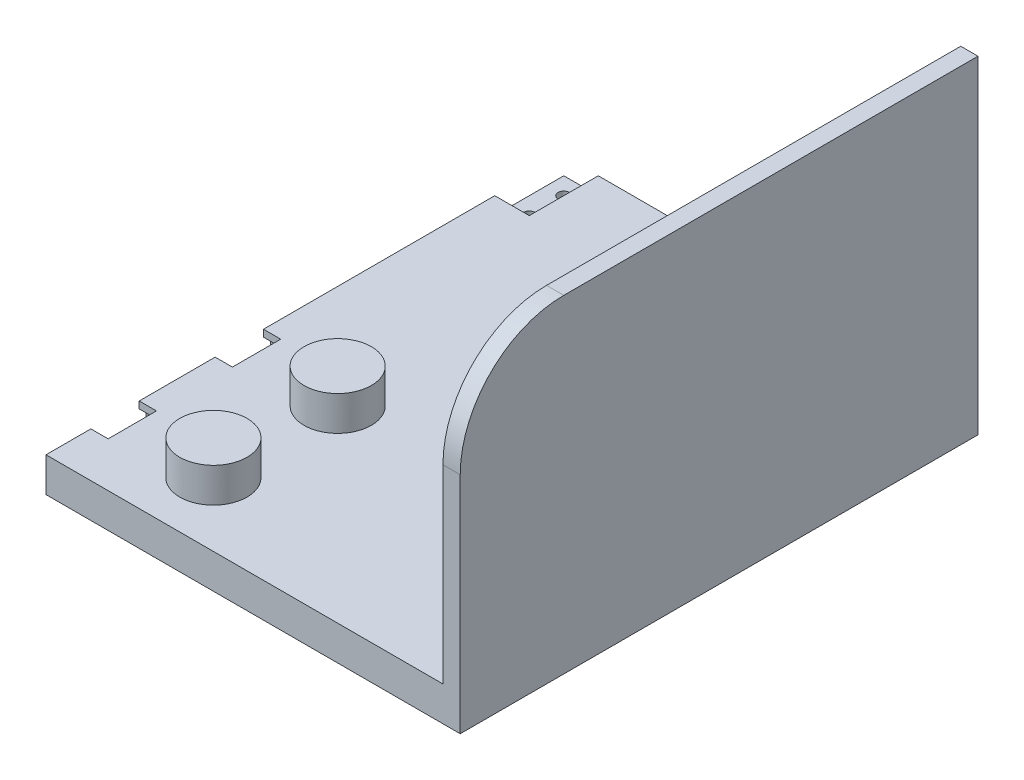
SolidWorks part; units mm, degrees
other "标注1"
sketch "草图4" plane through (-29.3482, 58.8293, 0) normal (-0.5287, 0.6909, -0.493) x (0.7294, 0.6669, 0.1525)
ref_plane "前视基准面" through (0, 0, 0) normal (0, 0, 1) x (1, 0, 0)
ref_plane "上视基准面" through (0, 0, 0) normal (0, 1, 0) x (1, 0, 0)
ref_plane "右视基准面" through (0, 0, 0) normal (1, 0, 0) x (0, 0, -1)
other "Configuration Table"
sketch "草图1" plane through (0, 0, 0) normal (0, 0, 1) x (1, 0, 0)
  line L1 (-29.3482, 58.8293) -> (90.6518, 58.8293)
  line L2 (-29.3482, 58.8293) -> (-29.3482, -36.1707)
  line L3 (-29.3482, -36.1707) -> (90.6518, -36.1707)
  line L4 (90.6518, 58.8293) -> (90.6518, -36.1707)
  dimension "D1" = 120
  dimension "D2" = 95
extrude "凸台-拉伸1" add sketch "草图1" along normal blind 150
sketch "草图2" plane through (0, 0, 150) normal (0, 0, 1) x (1, 0, 0)
  line L0 (-29.3482, -36.1707) -> (90.6518, -36.1707) construction
  line L1 (-29.3482, 58.8293) -> (85.6518, 58.8293)
  line L2 (-29.3482, 58.8293) -> (-29.3482, -26.1707)
  line L3 (-29.3482, -26.1707) -> (85.6518, -26.1707)
  line L4 (85.6518, 58.8293) -> (85.6518, -26.1707)
  line L5 (90.6518, -36.1707) -> (90.6518, 58.8293) construction
  dimension "D1" = 10
  dimension "D2" = 5
extrude "切除-拉伸1" cut sketch "草图2" against normal blind 150
sketch "草图3" plane through (90.6518, 0, 0) normal (1, 0, 0) x (0, 0, -1)
  line L0 (-150, -26.1707) -> (0, 58.8293)
  line L1 (-150, -36.1707) -> (-150, 58.8293) construction
  line L2 (0, 58.8293) -> (0, -36.1707)
  line L3 (0, -36.1707) -> (-150, -36.1707)
  line L4 (-150, -36.1707) -> (-150, -26.1707)
  line L5 (-150, -26.1707) -> (-150, 58.8293)
  line L6 (-150, 58.8293) -> (0, 58.8293)
  line M6 (0, 58.8293) -> (-150, 58.8293)
  line M7 (-150, 58.8293) -> (-150, -36.1707)
  dimension "D1" = 10
extrude "切除-拉伸2" cut sketch "草图3" against normal blind 150 contours L0 M7 M6
sketch "草图5" plane through (0, 0, 0) normal (0, 0, -1) x (-1, 0, 0)
  line L0 (-75.6518, -6.1707) -> (-85.6518, -6.1707)
  line L1 (-75.6518, -6.1707) -> (-75.6518, 28.8293)
  line L2 (-75.6518, 28.8293) -> (-85.6518, 28.8293)
  line L3 (-85.6518, -6.1707) -> (-85.6518, 28.8293)
  line L4 (-85.6518, -26.1707) -> (-85.6518, 58.8293) construction
  line L5 (29.3482, -36.1707) -> (-90.6518, -36.1707) construction
  line L6 (-90.6518, 58.8293) -> (-85.6518, 58.8293) construction
  circle A0 centre (-80.6518, 21.3293) radius 1.65
  circle A1 centre (-80.6518, 11.3293) radius 1.65
  circle A2 centre (-80.6518, 1.3293) radius 1.65
  dimension "D2" = 3.3
  dimension "D3" = 3.3
  dimension "D4" = 3.3
  dimension "D1" = 10
  dimension "D5" = 7.5
  dimension "D6" = 10
  dimension "D7" = 10
  dimension "D8" = 7.5
  dimension "D9" = 5
  dimension "D10" = 30
  dimension "D11" = 30
  dimension "D12" = 5
extrude "凸台-拉伸2" add sketch "草图5" against normal blind 5
sketch "草图6" plane through (0, -36.1707, 0) normal (0, -1, 0) x (-1, 0, 0)
  line L0 (-85.6518, -5) -> (-75.6518, -5)
  line L1 (-75.6518, -5) -> (-85.6518, -15)
  line L2 (-85.6518, -15) -> (-85.6518, -5)
  line L3 (-90.6518, -150) -> (-90.6518, 0) construction
  line L4 (29.3482, 0) -> (-90.6518, 0) construction
  dimension "D1" = 10
  dimension "D2" = 10
  dimension "D3" = 5
  dimension "D4" = 5
extrude "凸台-拉伸3" add sketch "草图6" along normal blind 3 from offset 33 offset against normal yes
sketch "草图7" plane through (0, -26.1707, 0) normal (0, 1, 0) x (1, 0, 0)
  line L0 (75.6518, -5) -> (85.6518, -5)
  line L1 (85.6518, -150) -> (85.6518, 0) construction
  line L2 (85.6518, -5) -> (85.6518, -15) construction
  line L3 (85.6518, -5) -> (85.6518, -15)
  line L4 (85.6518, 0) -> (85.6518, -150) construction
  line L5 (85.6518, -15) -> (75.6518, -5)
extrude "凸台-拉伸4" add sketch "草图7" along normal blind 3 from offset 52 contours L5 L0 L3
sketch "草图8" plane through (0, -26.1707, 0) normal (0, 1, 0) x (1, 0, 0)
  line L1 (-29.3482, 0) -> (-19.3482, 0)
  line L2 (-29.3482, 0) -> (-29.3482, -20)
  line L3 (-29.3482, -20) -> (-19.3482, -20)
  line L4 (-19.3482, 0) -> (-19.3482, -20)
  circle A0 centre (-24.3482, -5) radius 1.65
  circle A1 centre (-24.3482, -15) radius 1.65
  point P5 (-24.3482, 0)
  dimension "D3" = 3.3
  dimension "D4" = 3.3
  dimension "D5" = 5
  dimension "D1" = 20
  dimension "D2" = 10
  dimension "D6" = 10
  dimension "D7" = 5
extrude "切除-拉伸3" cut sketch "草图8" against normal blind 5
sketch "草图10" plane through (0, -26.1707, 0) normal (0, 1, 0) x (1, 0, 0)
  circle A0 centre (-24.3482, -5) radius 1.65
  circle A1 centre (-24.3482, -15) radius 1.65
extrude "切除-拉伸4" cut sketch "草图10" against normal through all
sketch "草图22" plane through (76.451, -36.1707, 11.6274) normal (0, -1, 0) x (-1, 0, 0)
  line L1 (105.7992, 11.6274) -> (-14.2008, 11.6274) construction
  line L2 (105.7992, -138.3726) -> (105.7992, 11.6274) construction
  circle A0 centre (75.7992, -83.8726) radius 7.75
  circle A1 centre (75.7992, -119.8726) radius 7.75
  dimension "D3" = 15.5
  dimension "D4" = 15.5
  dimension "D1" = 95.5
  dimension "D2" = 36
  dimension "D5" = 30
  dimension "D6" = 30
extrude "切除-拉伸8" cut sketch "草图22" against normal through all
sketch "草图24" plane through (76.451, -36.1707, 11.6274) normal (0, -1, 0) x (-1, 0, 0)
  circle A0 centre (75.7992, -83.8726) radius 9.75
  circle A1 centre (75.7992, -119.8726) radius 9.75
  circle A2 centre (75.7992, -83.8726) radius 7.75
  circle A3 centre (75.7992, -119.8726) radius 7.75
  dimension "D1" = 19.5
  dimension "D2" = 19.5
extrude "凸台-拉伸7" add sketch "草图24" against normal blind 15
sketch "草图26" plane through (-76.451, -21.1707, 11.6274) normal (0, 1, 0) x (1, 0, 0)
  circle A0 centre (77.1028, -83.8726) radius 9.75
  circle A1 centre (77.1028, -119.8726) radius 9.75
extrude "凸台-拉伸8" add sketch "草图26" along normal blind 5
sketch "草图31" plane through (0, -36.1707, 0) normal (0, -1, 0) x (1, 0, 0)
  line L0 (-29.3482, 150) -> (-29.3482, 0) construction
  line L1 (-29.3482, 142) -> (11.1518, 142)
  line L2 (-29.3482, 142) -> (-29.3482, 121)
  line L3 (-29.3482, 121) -> (11.1518, 121)
  line L4 (11.1518, 142) -> (11.1518, 121)
  line L5 (-29.3482, 0) -> (90.6518, 0) construction
  line L6 (-29.3482, 106) -> (11.1518, 106)
  line L7 (-29.3482, 106) -> (-29.3482, 85)
  line L8 (-29.3482, 85) -> (11.1518, 85)
  line L9 (11.1518, 106) -> (11.1518, 85)
  dimension "D1" = 21
  dimension "D2" = 21
  dimension "D3" = 85
  dimension "D4" = 15
  dimension "D5" = 40.5
  dimension "D6" = 40.5
extrude "切除-拉伸11" cut sketch "草图31" against normal blind 8
sketch "草图32" plane through (0, -36.1707, 0) normal (0, -1, 0) x (1, 0, 0)
  line L0 (-29.3482, 137) -> (-24.3482, 137)
  line L1 (-29.3482, 137) -> (-29.3482, 123)
  line L2 (-29.3482, 123) -> (-24.3482, 123)
  line L3 (-24.3482, 137) -> (-24.3482, 123)
  line L4 (-29.3482, 101) -> (-24.3482, 101)
  line L5 (-29.3482, 101) -> (-29.3482, 87)
  line L6 (-29.3482, 87) -> (-24.3482, 87)
  line L7 (-24.3482, 101) -> (-24.3482, 87)
  line L8 (11.1518, 142) -> (-29.3482, 142) construction
  line L9 (-29.3482, 142) -> (-29.3482, 121) construction
  line L10 (-29.3482, 106) -> (-29.3482, 85) construction
  line L11 (11.1518, 106) -> (-29.3482, 106) construction
  line L12 (-29.3482, 85) -> (11.1518, 85) construction
  line L13 (-29.3482, 121) -> (11.1518, 121) construction
  point P4 (-24.3482, 130)
  dimension "D1" = 5
  dimension "D2" = 5
  dimension "D3" = 5
  dimension "D4" = 5
  dimension "D5" = 2
  dimension "D6" = 2
extrude "切除-拉伸12" cut sketch "草图32" against normal through all
sketch "草图33" plane through (0, -36.1707, 0) normal (0, -1, 0) x (1, 0, 0)
  line L0 (-29.3482, 150) -> (90.6518, 150) construction
  line L1 (30.6518, 145) -> (85.6518, 145)
  line L2 (30.6518, 145) -> (30.6518, 90)
  line L3 (30.6518, 90) -> (85.6518, 90)
  line L4 (85.6518, 145) -> (85.6518, 90)
  line L5 (90.6518, 150) -> (90.6518, 0) construction
  dimension "D1" = 55
  dimension "D2" = 55
  dimension "D3" = 5
  dimension "D4" = 5
extrude "切除-拉伸13" cut sketch "草图33" against normal blind 1
sketch "草图34" plane through (90.6518, 0, 0) normal (1, 0, 0) x (0, 0, -1)
  line L0 (-150, -26.1707) -> (-150, 28.8293)
  line L1 (-120, 58.8293) -> (0, 58.8293)
  line L2 (-150, -26.1707) -> (0, 58.8293)
  arc A0 (-120, 58.8293) -> (-150, 28.8293) centre (-120, 28.8293) ccw
  dimension "D1" = 30
extrude "凸台-拉伸9" add sketch "草图34" against normal blind 5
